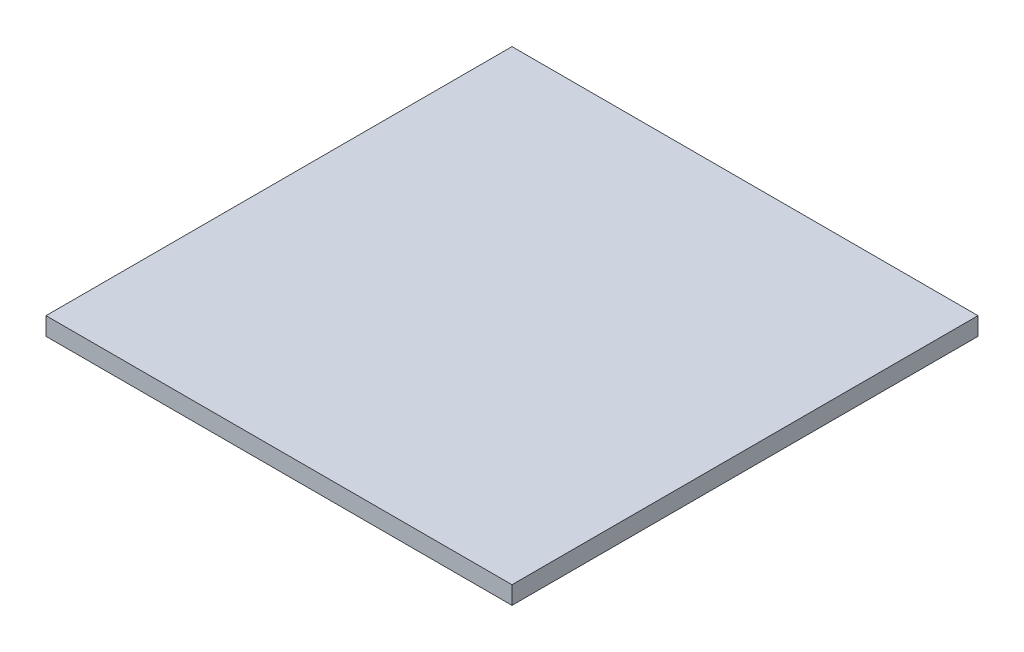
SolidWorks part; units mm, degrees
ref_plane "Front Plane" through (0, 0, 0) normal (0, 0, 1) x (1, 0, 0)
ref_plane "Top Plane" through (0, 0, 0) normal (0, 1, 0) x (1, 0, 0)
ref_plane "Right Plane" through (0, 0, 0) normal (1, 0, 0) x (0, 0, -1)
sketch "Sketch1" plane through (0, 0, 0) normal (0, 1, 0) x (1, 0, 0)
  line L1 (-82.5, -82.5) -> (82.5, -82.5)
  line L2 (-82.5, -82.5) -> (-82.5, 82.5)
  line L3 (-82.5, 82.5) -> (82.5, 82.5)
  line L4 (82.5, -82.5) -> (82.5, 82.5)
  line L5 (-82.5, -82.5) -> (82.5, 82.5) construction
  line L6 (-82.5, 82.5) -> (82.5, -82.5) construction
  point P0 (0, 0)
  dimension "D1" = 165
extrude "Boss-Extrude1" add sketch "Sketch1" along normal blind 6.35
